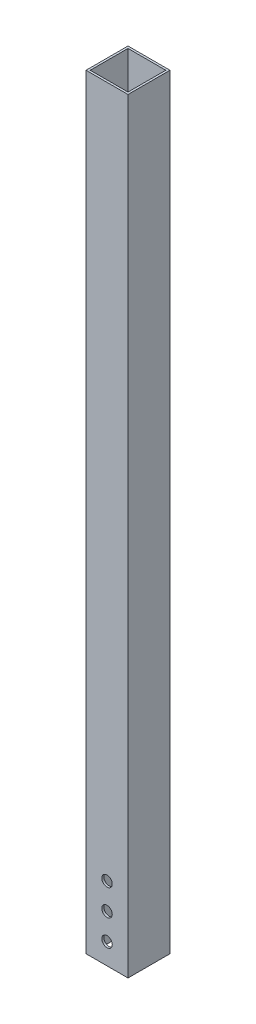
SolidWorks part; units mm, degrees
material "6061 合金"
ref_plane "前视基准面" through (0, 0, 0) normal (0, 0, 1) x (1, 0, 0)
ref_plane "上视基准面" through (0, 0, 0) normal (0, 1, 0) x (1, 0, 0)
ref_plane "右视基准面" through (0, 0, 0) normal (1, 0, 0) x (0, 0, -1)
sketch "草图1" plane through (0, 0, 0) normal (0, 0, 1) x (1, 0, 0)
  line L0 (0, 0) -> (0, 364.53)
  dimension "D1" = 364.53
other "方形管 20 X 20 X 2(1)"
ref_plane "基准面1" through (0, 0, 0) normal (0, 1, 0) x (-1, 0, 0)
sketch "Sketch1" plane through (0, 0, 0) normal (0, 1, 0) x (-1, 0, 0)
  line L0 (-9, -9) -> (9, -9)
  line L1 (-9, -9) -> (-9, 9)
  line L2 (9, 9) -> (-9, 9)
  line L3 (9, 9) -> (9, -9)
  line L4 (-10, -10) -> (10, -10)
  line L5 (-10, -10) -> (-10, 10)
  line L6 (10, 10) -> (-10, 10)
  line L7 (10, 10) -> (10, -10)
  point P0 (-10, 0)
  point P1 (10, 0)
  point P2 (0, 10)
  point P3 (0, -10)
  point P4 (0, 0)
  point P5 (-10, -10)
  point P6 (10, -10)
  point P7 (10, 10)
  point P8 (-10, 10)
  point P10 (0, 0)
  dimension "D1" = 1
  dimension "D2" = 1
  dimension "D3" = 1
  dimension "Thickness" = 1
  dimension "V_leg" = 20
sketch "草图2" plane through (0, 0, 10) normal (0, 0, 1) x (1, 0, 0)
  line L0 (0, 0) -> (0, 364.53) construction
  line L1 (-10, 364.53) -> (10, 364.53) construction
  line L2 (-10, 0) -> (10, 0) construction
  circle A0 centre (0, 10) radius 2.5
  circle A1 centre (0, 22.5) radius 2.5
  circle A2 centre (0, 35) radius 2.5
  dimension "D1" = 12.5
  dimension "D2" = 12.5
  dimension "D3" = 10
  dimension "D4" = 5
extrude "切除-拉伸1" cut sketch "草图2" against normal through all
